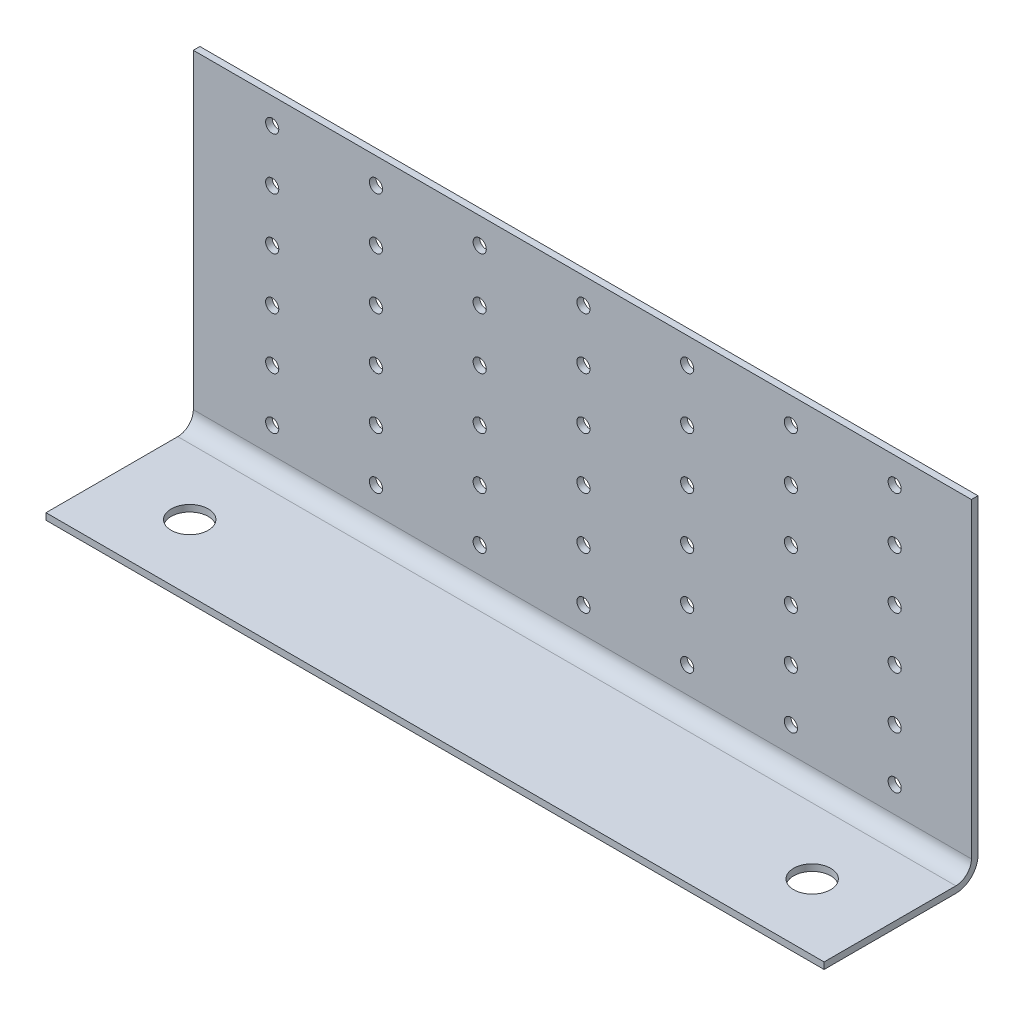
SolidWorks part; units mm, degrees
ref_plane "前视" through (0, 0, 0) normal (0, 0, 1) x (1, 0, 0)
ref_plane "上视" through (0, 0, 0) normal (0, 1, 0) x (1, 0, 0)
ref_plane "右视" through (0, 0, 0) normal (1, 0, 0) x (0, 0, -1)
sketch "Sketch2" plane through (0, 0, 0) normal (1, 0, 0) x (0, 0, -1)
  line L0 (-25.3233, -22.8977) -> (0.0767, -22.8977)
  line L1 (3.0767, -19.8977) -> (3.0767, 40.1023)
  arc A0 (3.0767, -19.8977) -> (0.0767, -22.8977) centre (0.0767, -19.8977) cw
  dimension "D1" = 3
  dimension "D2" = 25.4
  dimension "D3" = 60
extrude "Extrude-Thin1" add sketch "Sketch2" along normal blind 150 thin
sketch "Sketch5" plane through (0, -22.8977, 0) normal (0, 1, 0) x (1, 0, 0)
  line L0 (150, -25.3233) -> (0, -25.3233) construction
  line L1 (0, -25.3233) -> (0, 0.0767) construction
  line L2 (150, -25.3233) -> (150, 0.0767) construction
  circle A0 centre (15, -12.6233) radius 3.575
  circle A1 centre (135, -12.6233) radius 3.575
  point P0 (15, -12.6233)
  point P5 (135, -12.6233)
  point P8 (15, -12.6233)
  dimension "D4" = 7.15
  dimension "D5" = 7.15
  dimension "D1" = 12.7
  dimension "D2" = 15
  dimension "D3" = 15
extrude "Cut-Extrude1" cut sketch "Sketch5" against normal through all
sketch "Sketch6" plane through (0, 0, -3.0767) normal (0, 0, 1) x (1, 0, 0)
  line L0 (150, 40.1023) -> (0, 40.1023) construction
  circle A0 centre (15.2054, 35.1023) radius 1.27
  point P0 (15.2054, 35.1023)
  dimension "D2" = 2.54
  dimension "D1" = 5
extrude "Cut-Extrude2" cut sketch "Sketch6" against normal through all
pattern_linear "LPattern2" count 7 spacing 20 along (1, 0, 0) of "Cut-Extrude2"
pattern_linear "LPattern3" count 6 spacing 10 along (0, -1, 0) of "LPattern2", "Cut-Extrude2"
